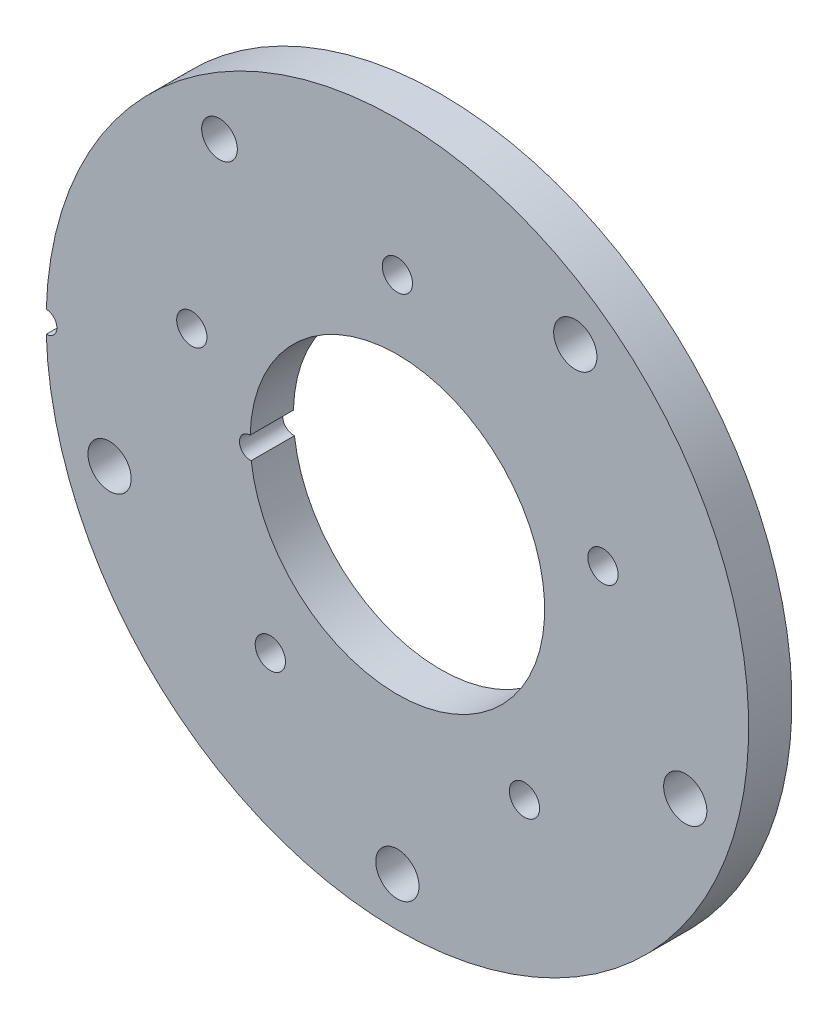
SolidWorks part; units mm, degrees
ref_plane "前视基准面" through (0, 0, 0) normal (0, 0, 1) x (1, 0, 0)
ref_plane "上视基准面" through (0, 0, 0) normal (0, 1, 0) x (1, 0, 0)
ref_plane "右视基准面" through (0, 0, 0) normal (1, 0, 0) x (0, 0, -1)
sketch "草图1" plane through (0, 0, 0) normal (0, 0, 1) x (1, 0, 0)
  line L0 (-26.8908, -7.9995) -> (-0.2612, -27.347) construction
  line L1 (-13.576, -17.6733) -> (-5.2543, -6.2194) construction
  circle A0 centre (-0.2612, 0.653) radius 32.5
  circle A1 centre (-0.2612, 0.653) radius 13.625
  circle A2 centre (-0.2612, -27.347) radius 2
  circle A3 centre (-26.8908, -7.9995) radius 2
  circle A4 centre (-16.7192, 23.3054) radius 1.65
  circle A5 centre (16.1968, 23.3054) radius 2
  circle A6 centre (26.3684, -7.9995) radius 2
  circle A7 centre (-0.2612, 0.653) radius 20 construction
  circle A8 centre (-12.0169, -15.5274) radius 1.4
  circle A9 centre (-19.2823, 6.8333) radius 1.4
  circle A10 centre (-0.2612, 20.653) radius 1.4
  circle A11 centre (18.7599, 6.8333) radius 1.4
  circle A12 centre (11.4945, -15.5274) radius 1.4
  dimension "D1" = 65
  dimension "D2" = 40
  dimension "D3" = 27.25
  dimension "D4" = 2.8
  dimension "D5" = 5
extrude "凸台-拉伸1" add sketch "草图1" along normal blind 4 contours A0
sketch "草图2" plane through (0, 0, 4) normal (0, 0, 1) x (1, 0, 0)
  circle A0 centre (-13.8705, 0) radius 1
  circle A1 centre (-0.2612, 0.653) radius 13.625 construction
  circle A2 centre (-32.7612, 0.653) radius 1
  circle A3 centre (-0.2612, 0.653) radius 32.5 construction
extrude "切除-拉伸1" cut sketch "草图2" against normal blind 10
